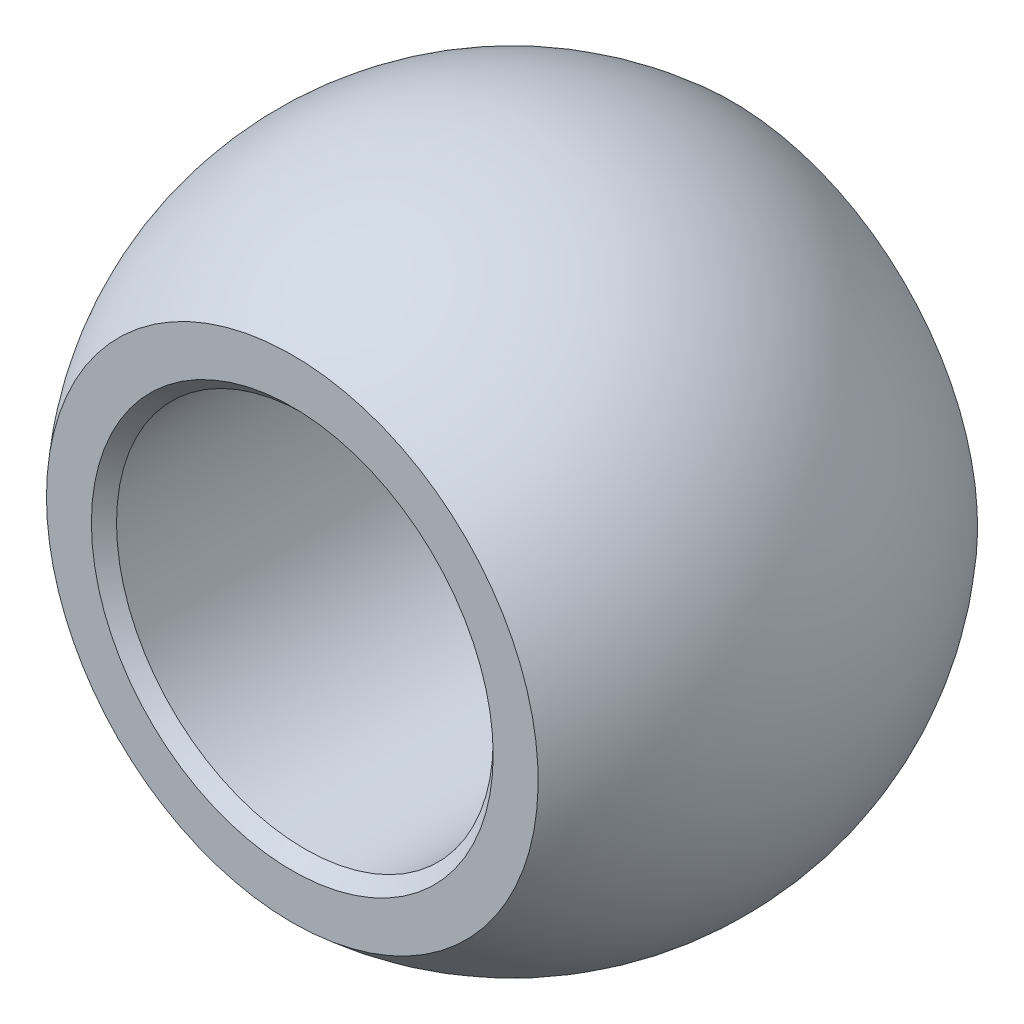
SolidWorks part; units mm, degrees
ref_plane "Front" through (0, 0, 0) normal (0, 0, 1) x (1, 0, 0)
ref_plane "Top" through (0, 0, 0) normal (0, 1, 0) x (1, 0, 0)
ref_plane "Right" through (0, 0, 0) normal (1, 0, 0) x (0, 0, -1)
sketch "Sketch7" plane through (0, 0, 0) normal (0, 0, 1) x (1, 0, 0)
  line L0 (0, 16.6751) -> (0, -16.6751)
  line L1 (0, 22.1145) -> (0, -23.7243) construction
  arc A0 (0, -16.6751) -> (0, 16.6751) centre (0, 0) ccw
  dimension "D1" = 33.3502
  dimension "D2" = 16.6751
sketch "Sketch8" plane through (0, 0, 0) normal (1, 0, 0) x (0, 0, -1)
  line L2 (-11.1125, 50.8) -> (-11.1125, -50.8)
  line L4 (11.1125, 50.8) -> (11.1125, -50.8)
  line L5 (11.1125, 50.8) -> (22.225, 50.8)
  line L6 (22.225, 50.8) -> (22.225, -50.8)
  line L7 (22.225, -50.8) -> (11.1125, -50.8)
  line L8 (-11.1125, -50.8) -> (-22.225, -50.8)
  line L9 (-22.225, -50.8) -> (-22.225, 50.8)
  line L10 (-22.225, 50.8) -> (-11.1125, 50.8)
  dimension "D1" = 101.6
  dimension "D2" = 44.45
  dimension "D3" = 22.225
revolve "Revolve1" add sketch "Sketch7" angle 360 about L1
extrude "Cut-Extrude3" cut sketch "Sketch8" against normal through all and the other way through all
sketch "Sketch10" plane through (0, 0, 0) normal (0, 0, 1) x (1, 0, 0)
  circle A1 centre (0, 0) radius 12.4327 construction
  circle A2 centre (0, 0) radius 9.525
  circle A3 centre (0, 0) radius 12.4327 construction
extrude "Cut-Extrude4" cut sketch "Sketch10" against normal through all and the other way through all
chamfer "Chamfer1" distance 0.635 angle 45 2 edges at (9.525, 0, 11.1125) (9.525, 0, -11.1125)
